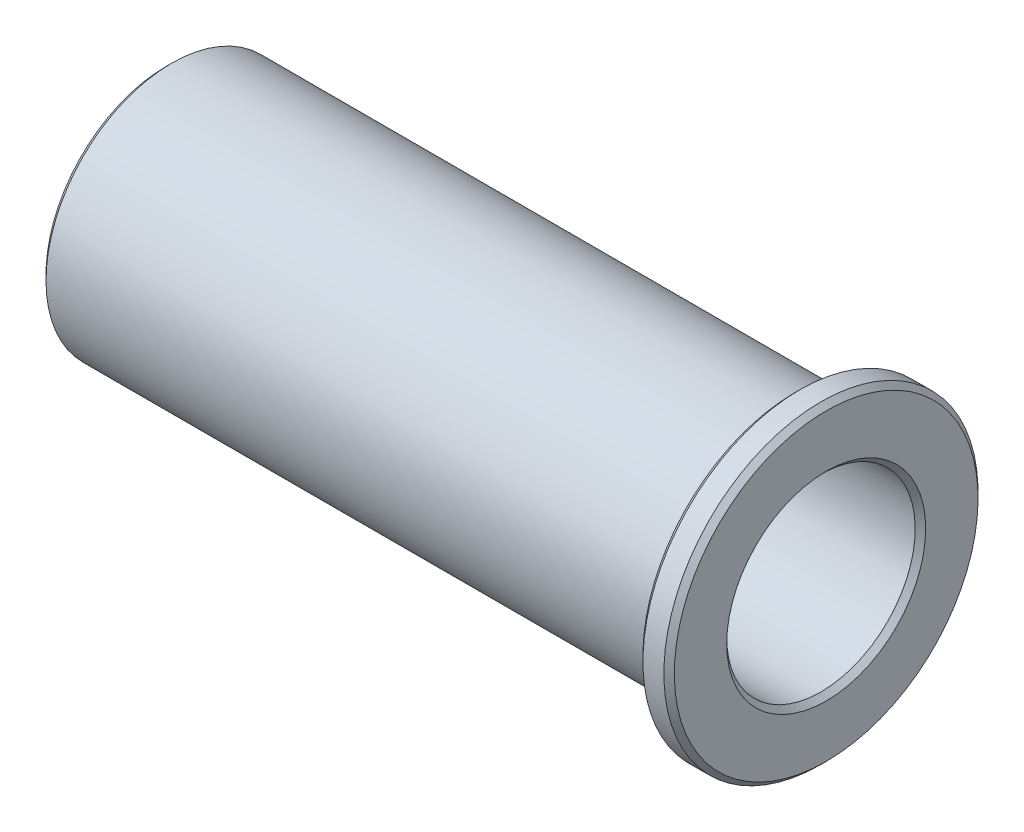
SolidWorks part; units mm, degrees
material "AISI 304"
ref_plane "Спереди" through (0, 0, 0) normal (0, 0, 1) x (1, 0, 0)
ref_plane "Сверху" through (0, 0, 0) normal (0, 1, 0) x (1, 0, 0)
ref_plane "Справа" through (0, 0, 0) normal (1, 0, 0) x (0, 0, -1)
other "Configuration Table"
sketch "Эскиз1" plane through (0, 0, 0) normal (0, 0, 1) x (1, 0, 0)
  line L0 (0, 0) -> (19, 0) construction
  line L1 (0, 9) -> (0, 12)
  line L2 (0, 12) -> (60, 12)
  line L3 (60, 12) -> (60, 15)
  line L4 (60, 15) -> (63, 15)
  line L5 (63, 15) -> (63, 9)
  line L6 (0, 9) -> (63, 9)
  line L7 (0, 9) -> (0, 0) construction
  line L8 (63, 10) -> (0, 10) construction
  dimension "D1" = 24
  dimension "D2" = 30
  dimension "D3" = 3
  dimension "D4" = 63
  dimension "D5" = 18
  dimension "D6" = 1
revolve "Повернуть1" add sketch "Эскиз1" angle 360 about L0
chamfer "Фаска1" distance 0.5 angle 45 5 edges at (63, -15, 0) (60, -15, 0) (0, -12, 0) (63, -9, 0) (0, -9, 0)
